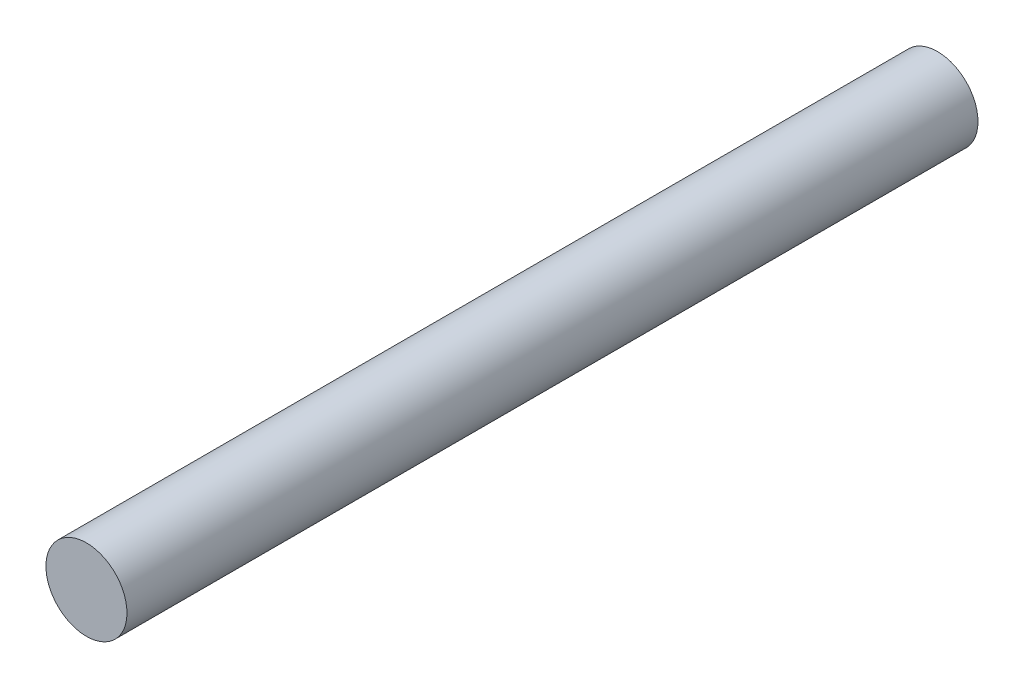
SolidWorks part; units mm, degrees
ref_plane "Спереди" through (0, 0, 0) normal (0, 0, 1) x (1, 0, 0)
ref_plane "Сверху" through (0, 0, 0) normal (0, 1, 0) x (1, 0, 0)
ref_plane "Справа" through (0, 0, 0) normal (1, 0, 0) x (0, 0, -1)
sketch "Эскиз1" plane through (0, 0, 0) normal (0, 0, 1) x (1, 0, 0)
  circle A0 centre (0, 0) radius 10
extrude "Бобышка-Вытянуть1" add sketch "Эскиз1" along normal blind 210
